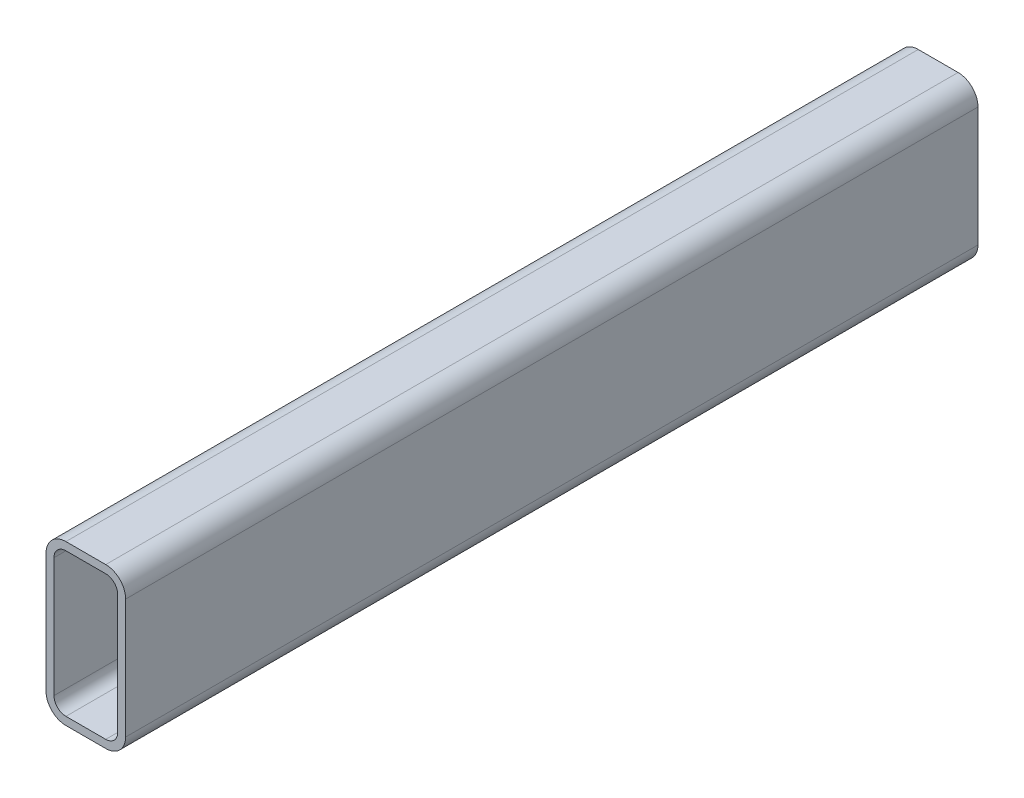
SolidWorks part; units mm, degrees
material "Q355"
ref_plane "前视基准面" through (0, 0, 0) normal (0, 0, 1) x (1, 0, 0)
ref_plane "上视基准面" through (0, 0, 0) normal (0, 1, 0) x (1, 0, 0)
ref_plane "右视基准面" through (0, 0, 0) normal (1, 0, 0) x (0, 0, -1)
sketch "尺寸草图" plane through (0, 0, 0) normal (0, 0, 1) x (1, 0, 0)
  line L0 (-25.8313, 0) -> (32, 0) construction
  line L1 (0, 56.0755) -> (0, -63.3818) construction
  line L2 (-20, 72) -> (20, 72)
  line L3 (-20, 80) -> (20, 80)
  line L4 (-40, 60) -> (-40, -60)
  line L5 (-20, -80) -> (20, -80)
  line L6 (40, 60) -> (40, -60)
  line L7 (32, 60) -> (32, -60)
  line L8 (-20, -72) -> (20, -72)
  line L9 (-32, 60) -> (-32, -60)
  line L10 (-40, 80) -> (-40, -80) construction
  line L11 (-40, -80) -> (40, -80) construction
  line L12 (-32, -72) -> (32, -72) construction
  line L13 (-32, 72) -> (-32, -72) construction
  line L14 (32, 72) -> (32, -72) construction
  line L15 (40, 80) -> (40, -80) construction
  line L16 (-32, 72) -> (32, 72) construction
  line L17 (-40, 80) -> (40, 80) construction
  arc A0 (-40, -60) -> (-20, -80) centre (-20, -60) ccw
  arc A1 (-20, -72) -> (-32, -60) centre (-20, -60) cw
  arc A2 (32, -60) -> (20, -72) centre (20, -60) cw
  arc A3 (20, -80) -> (40, -60) centre (20, -60) ccw
  arc A4 (20, 72) -> (32, 60) centre (20, 60) cw
  arc A5 (20, 80) -> (40, 60) centre (20, 60) cw
  arc A6 (-20, 72) -> (-32, 60) centre (-20, 60) ccw
  arc A7 (-20, 80) -> (-40, 60) centre (-20, 60) ccw
  dimension "D2" = 20
  dimension "H" = 160
  dimension "B" = 80
  dimension "t" = 8
extrude "凸台-拉伸1" add sketch "尺寸草图" along normal mid plane 856
